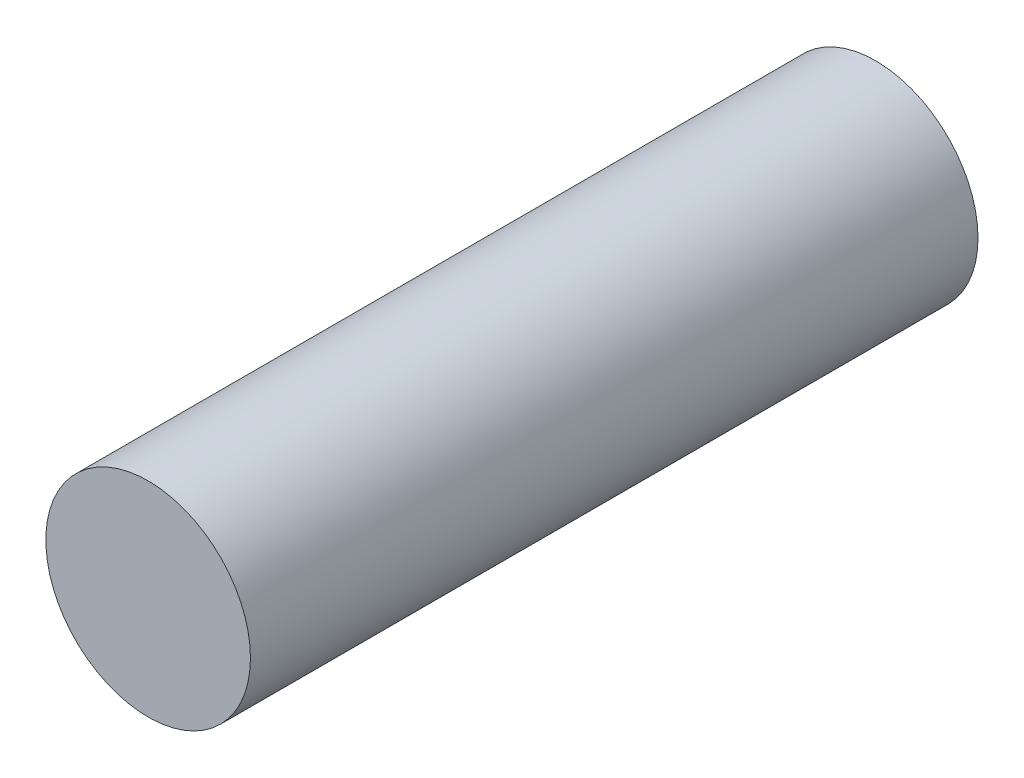
SolidWorks part; units mm, degrees
ref_plane "前视基准面" through (0, 0, 0) normal (0, 0, 1) x (1, 0, 0)
ref_plane "上视基准面" through (0, 0, 0) normal (0, 1, 0) x (1, 0, 0)
ref_plane "右视基准面" through (0, 0, 0) normal (1, 0, 0) x (0, 0, -1)
other "Configuration Table"
sketch "草图1" plane through (0, 0, 0) normal (0, 0, 1) x (1, 0, 0)
  circle A0 centre (0, 0) radius 4.5
extrude "凸台-拉伸1" add sketch "草图1" against normal blind 32
